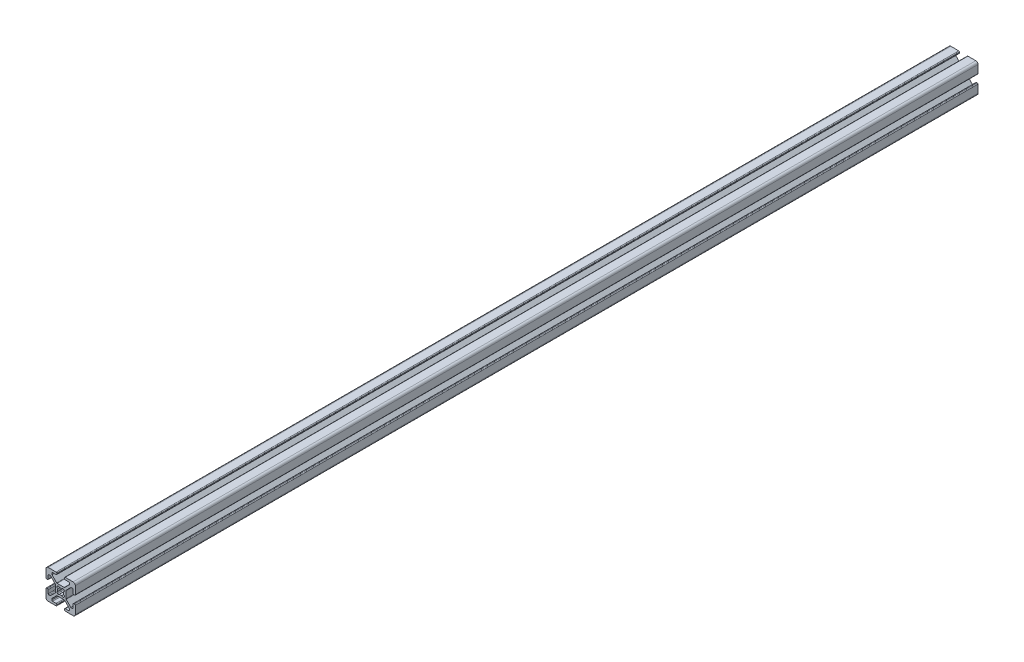
SolidWorks part; units mm, degrees
material "1060 Alloy"
ref_plane "Front Plane" through (0, 0, 0) normal (0, 0, 1) x (1, 0, 0)
ref_plane "Top Plane" through (0, 0, 0) normal (0, 1, 0) x (1, 0, 0)
ref_plane "Right Plane" through (0, 0, 0) normal (1, 0, 0) x (0, 0, -1)
sketch "Sketch2" plane through (0, 0, 0) normal (0, 0, 1) x (1, 0, 0)
  line L0 (-10, -3.138) -> (-10, -8.5)
  line L1 (-8.5, -10) -> (-3.138, -10)
  line L2 (-2.63, -9.492) -> (-2.63, -9.008)
  line L3 (-3.138, -8.5) -> (-5.487, -8.5)
  line L4 (-5.995, -7.992) -> (-5.995, -7.2662)
  line L5 (-5.8462, -6.907) -> (-2.743, -3.8038)
  line L6 (-2.3838, -3.655) -> (2.3841, -3.655)
  line L7 (2.7433, -3.8038) -> (5.8462, -6.9067)
  line L8 (5.995, -7.2659) -> (5.995, -7.992)
  line L9 (5.487, -8.5) -> (3.138, -8.5)
  line L10 (2.63, -9.008) -> (2.63, -9.492)
  line L11 (3.138, -10) -> (8.5, -10)
  line L12 (10, -8.5) -> (10, -3.138)
  line L13 (9.492, -2.63) -> (9.008, -2.63)
  line L14 (8.5, -3.138) -> (8.5, -5.487)
  line L15 (7.992, -5.995) -> (7.2662, -5.995)
  line L16 (6.907, -5.8462) -> (3.8038, -2.743)
  line L17 (3.655, -2.3838) -> (3.655, 2.3841)
  line L18 (3.8038, 2.7433) -> (6.9067, 5.8462)
  line L19 (7.2659, 5.995) -> (7.992, 5.995)
  line L20 (8.5, 5.487) -> (8.5, 3.138)
  line L21 (9.008, 2.63) -> (9.492, 2.63)
  line L22 (10, 3.138) -> (10, 8.5)
  line L23 (8.5, 10) -> (3.138, 10)
  line L24 (2.63, 9.492) -> (2.63, 9.008)
  line L25 (3.138, 8.5) -> (5.487, 8.5)
  line L26 (5.995, 7.992) -> (5.995, 7.2662)
  line L27 (5.8462, 6.907) -> (2.743, 3.8038)
  line L28 (2.3838, 3.655) -> (-2.3841, 3.655)
  line L29 (-2.7433, 3.8038) -> (-5.8462, 6.9067)
  line L30 (-5.995, 7.2659) -> (-5.995, 7.992)
  line L31 (-5.487, 8.5) -> (-3.138, 8.5)
  line L32 (-2.63, 9.008) -> (-2.63, 9.492)
  line L33 (-3.138, 10) -> (-8.5, 10)
  line L34 (-10, 8.5) -> (-10, 3.138)
  line L35 (-9.492, 2.63) -> (-9.008, 2.63)
  line L36 (-8.5, 3.138) -> (-8.5, 5.487)
  line L37 (-7.992, 5.995) -> (-7.2662, 5.995)
  line L38 (-6.907, 5.8462) -> (-3.8038, 2.743)
  line L39 (-3.655, 2.3838) -> (-3.655, -2.3841)
  line L40 (-3.8038, -2.7433) -> (-6.9067, -5.8462)
  line L41 (-7.2659, -5.995) -> (-7.992, -5.995)
  line L42 (-8.5, -5.487) -> (-8.5, -3.138)
  line L43 (-9.008, -2.63) -> (-9.492, -2.63)
  line L44 (-2.1245, 2.3045) -> (-2.3045, 2.1245)
  line L45 (2.3045, 2.1245) -> (2.1245, 2.3045)
  line L46 (2.1245, -2.3045) -> (2.3045, -2.1245)
  line L47 (-2.3045, -2.1245) -> (-2.1245, -2.3045)
  arc A0 (-10, -8.5) -> (-8.5, -10) centre (-8.5, -8.5) ccw
  arc A1 (-3.138, -10) -> (-2.63, -9.492) centre (-3.138, -9.492) ccw
  arc A2 (-2.63, -9.008) -> (-3.138, -8.5) centre (-3.138, -9.008) ccw
  arc A3 (-5.995, -7.992) -> (-5.487, -8.5) centre (-5.487, -7.992) ccw
  arc A4 (-5.8462, -6.907) -> (-5.995, -7.2662) centre (-5.487, -7.2662) ccw
  arc A5 (-2.3838, -3.655) -> (-2.743, -3.8038) centre (-2.3838, -4.163) ccw
  arc A6 (2.7433, -3.8038) -> (2.3841, -3.655) centre (2.3841, -4.163) ccw
  arc A7 (5.995, -7.2659) -> (5.8462, -6.9067) centre (5.487, -7.2659) ccw
  arc A8 (5.487, -8.5) -> (5.995, -7.992) centre (5.487, -7.992) ccw
  arc A9 (3.138, -8.5) -> (2.63, -9.008) centre (3.138, -9.008) ccw
  arc A10 (2.63, -9.492) -> (3.138, -10) centre (3.138, -9.492) ccw
  arc A11 (8.5, -10) -> (10, -8.5) centre (8.5, -8.5) ccw
  arc A12 (10, -3.138) -> (9.492, -2.63) centre (9.492, -3.138) ccw
  arc A13 (9.008, -2.63) -> (8.5, -3.138) centre (9.008, -3.138) ccw
  arc A14 (7.992, -5.995) -> (8.5, -5.487) centre (7.992, -5.487) ccw
  arc A15 (6.907, -5.8462) -> (7.2662, -5.995) centre (7.2662, -5.487) ccw
  arc A16 (3.655, -2.3838) -> (3.8038, -2.743) centre (4.163, -2.3838) ccw
  arc A17 (3.8038, 2.7433) -> (3.655, 2.3841) centre (4.163, 2.3841) ccw
  arc A18 (7.2659, 5.995) -> (6.9067, 5.8462) centre (7.2659, 5.487) ccw
  arc A19 (8.5, 5.487) -> (7.992, 5.995) centre (7.992, 5.487) ccw
  arc A20 (8.5, 3.138) -> (9.008, 2.63) centre (9.008, 3.138) ccw
  arc A21 (9.492, 2.63) -> (10, 3.138) centre (9.492, 3.138) ccw
  arc A22 (10, 8.5) -> (8.5, 10) centre (8.5, 8.5) ccw
  arc A23 (3.138, 10) -> (2.63, 9.492) centre (3.138, 9.492) ccw
  arc A24 (2.63, 9.008) -> (3.138, 8.5) centre (3.138, 9.008) ccw
  arc A25 (5.995, 7.992) -> (5.487, 8.5) centre (5.487, 7.992) ccw
  arc A26 (5.8462, 6.907) -> (5.995, 7.2662) centre (5.487, 7.2662) ccw
  arc A27 (2.3838, 3.655) -> (2.743, 3.8038) centre (2.3838, 4.163) ccw
  arc A28 (-2.7433, 3.8038) -> (-2.3841, 3.655) centre (-2.3841, 4.163) ccw
  arc A29 (-5.995, 7.2659) -> (-5.8462, 6.9067) centre (-5.487, 7.2659) ccw
  arc A30 (-5.487, 8.5) -> (-5.995, 7.992) centre (-5.487, 7.992) ccw
  arc A31 (-3.138, 8.5) -> (-2.63, 9.008) centre (-3.138, 9.008) ccw
  arc A32 (-2.63, 9.492) -> (-3.138, 10) centre (-3.138, 9.492) ccw
  arc A33 (-8.5, 10) -> (-10, 8.5) centre (-8.5, 8.5) ccw
  arc A34 (-10, 3.138) -> (-9.492, 2.63) centre (-9.492, 3.138) ccw
  arc A35 (-9.008, 2.63) -> (-8.5, 3.138) centre (-9.008, 3.138) ccw
  arc A36 (-7.992, 5.995) -> (-8.5, 5.487) centre (-7.992, 5.487) ccw
  arc A37 (-6.907, 5.8462) -> (-7.2662, 5.995) centre (-7.2662, 5.487) ccw
  arc A38 (-3.655, 2.3838) -> (-3.8038, 2.743) centre (-4.163, 2.3838) ccw
  arc A39 (-3.8038, -2.7433) -> (-3.655, -2.3841) centre (-4.163, -2.3841) ccw
  arc A40 (-7.2659, -5.995) -> (-6.9067, -5.8462) centre (-7.2659, -5.487) ccw
  arc A41 (-8.5, -5.487) -> (-7.992, -5.995) centre (-7.992, -5.487) ccw
  arc A42 (-8.5, -3.138) -> (-9.008, -2.63) centre (-9.008, -3.138) ccw
  arc A43 (-9.492, -2.63) -> (-10, -3.138) centre (-9.492, -3.138) ccw
  arc A44 (-1.9358, 0.8037) -> (-1.9358, -0.8037) centre (0, 0) ccw
  arc A45 (-2.3045, 2.1245) -> (-1.9358, 0.8037) centre (-1.748, 1.568) ccw
  arc A46 (-0.8037, 1.9358) -> (-2.1245, 2.3045) centre (-1.568, 1.748) ccw
  arc A47 (0.8037, 1.9358) -> (-0.8037, 1.9358) centre (0, 0) ccw
  arc A48 (2.1245, 2.3045) -> (0.8037, 1.9358) centre (1.568, 1.748) ccw
  arc A49 (1.9358, 0.8037) -> (2.3045, 2.1245) centre (1.748, 1.568) ccw
  arc A50 (1.9358, -0.8037) -> (1.9358, 0.8037) centre (0, 0) ccw
  arc A51 (2.3045, -2.1245) -> (1.9358, -0.8037) centre (1.748, -1.568) ccw
  arc A52 (0.8037, -1.9358) -> (2.1245, -2.3045) centre (1.568, -1.748) ccw
  arc A53 (-0.8037, -1.9358) -> (0.8037, -1.9358) centre (0, 0) ccw
  arc A54 (-2.1245, -2.3045) -> (-0.8037, -1.9358) centre (-1.568, -1.748) ccw
  arc A55 (-1.9358, -0.8037) -> (-2.3045, -2.1245) centre (-1.748, -1.568) ccw
extrude "Boss-Extrude1" add sketch "Sketch2" against normal blind 616
